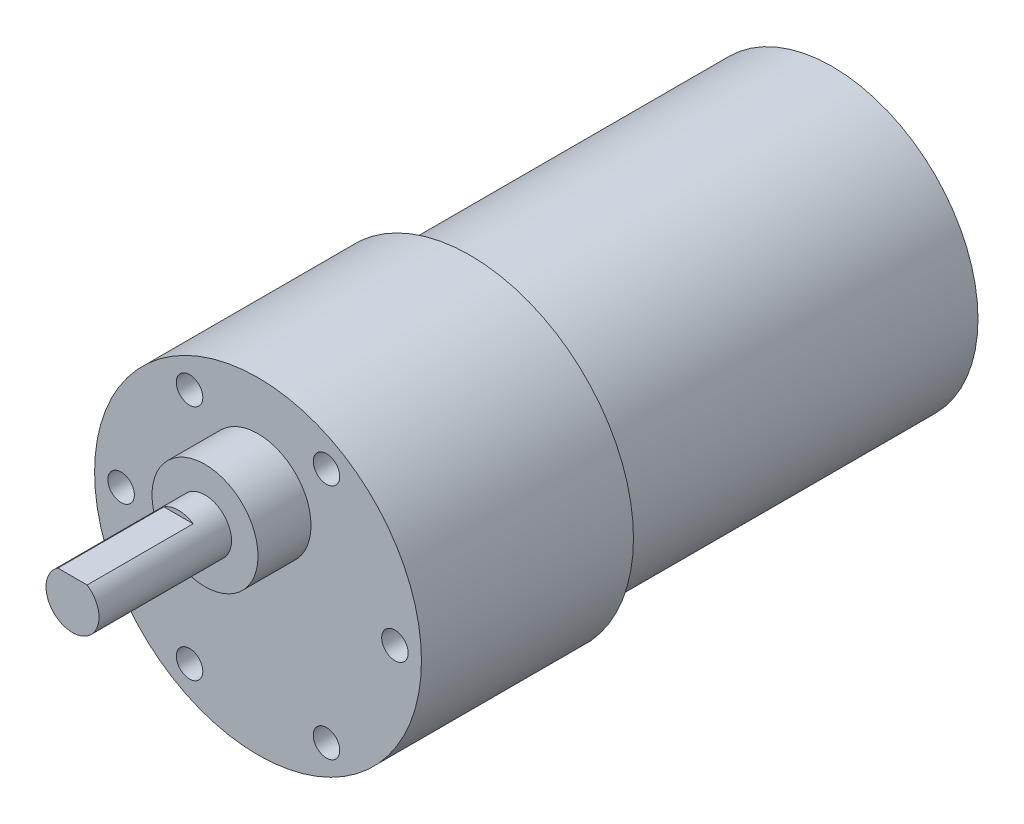
SolidWorks part; units mm, degrees
ref_plane "Front Plane" through (0, 0, 0) normal (0, 0, 1) x (1, 0, 0)
ref_plane "Top Plane" through (0, 0, 0) normal (0, 1, 0) x (1, 0, 0)
ref_plane "Right Plane" through (0, 0, 0) normal (1, 0, 0) x (0, 0, -1)
sketch "Sketch1" plane through (0, 0, 0) normal (0, 0, 1) x (1, 0, 0)
  circle A0 centre (0, 0) radius 16.5
  dimension "D1" = 33
extrude "Boss-Extrude1" add sketch "Sketch1" along normal blind 29
sketch "Sketch2" plane through (0, 0, 29) normal (0, 0, 1) x (1, 0, 0)
  circle A0 centre (0, 0) radius 18.5
  dimension "D1" = 37
extrude "Boss-Extrude2" add sketch "Sketch2" along normal blind 24
sketch "Sketch3" plane through (0, 0, 53) normal (0, 0, 1) x (1, 0, 0)
  circle A0 centre (0, 7) radius 6
  point P3 (0, 0)
  point P5 (0, 7.5543)
  point P7 (0, 0)
  point P8 (-2.7552, 6.435)
  dimension "D1" = 12
  dimension "D2" = 7
  dimension "D3" = 0
extrude "Boss-Extrude3" add sketch "Sketch3" along normal blind 6
sketch "Sketch4" plane through (0, 0, 59) normal (0, 0, 1) x (1, 0, 0)
  circle A0 centre (0, 7) radius 3
  point P4 (0, 7)
  dimension "D1" = 6
extrude "Boss-Extrude5" add sketch "Sketch4" along normal blind 3 contours A0
sketch "Sketch5" plane through (0, 0, 62) normal (0, 0, 1) x (1, 0, 0)
  line L3 (-1.6583, 9.5) -> (1.6583, 9.5)
  arc A3 (-1.6583, 9.5) -> (1.6583, 9.5) centre (0, 7) ccw
  point P1 (0, 6.9221)
  point P2 (0.182, 7.4172)
  point P3 (0, 7)
  dimension "D1" = 6
extrude "Boss-Extrude6" add sketch "Sketch5" along normal blind 12
sketch "Sketch6" plane through (0, 0, 0) normal (0, 0, -1) x (-1, 0, 0)
  circle A0 centre (0, 0) radius 16.5
  dimension "D1" = 33
extrude "Boss-Extrude8" add sketch "Sketch6" along normal blind 12
sketch "Sketch7" plane through (0, 0, 53) normal (0, 0, 1) x (1, 0, 0)
  circle A0 centre (-15.5, 0) radius 1.5
  circle A1 centre (7.75, 13.4234) radius 1.5
  circle A2 centre (7.75, -13.4234) radius 1.5
  circle A3 centre (15.5, 0) radius 1.5
  circle A4 centre (-7.75, -13.4234) radius 1.5
  circle A5 centre (-7.75, 13.4234) radius 1.5
  point P9 (0, 0)
  point P17 (0, 0)
  dimension "D1" = 3
  dimension "D4" = 3
  dimension "D2" = 15.5
  dimension "D3" = 3
  dimension "D5" = 15.5
  dimension "D6" = 3
extrude "Cut-Extrude1" cut sketch "Sketch7" against normal blind 5
